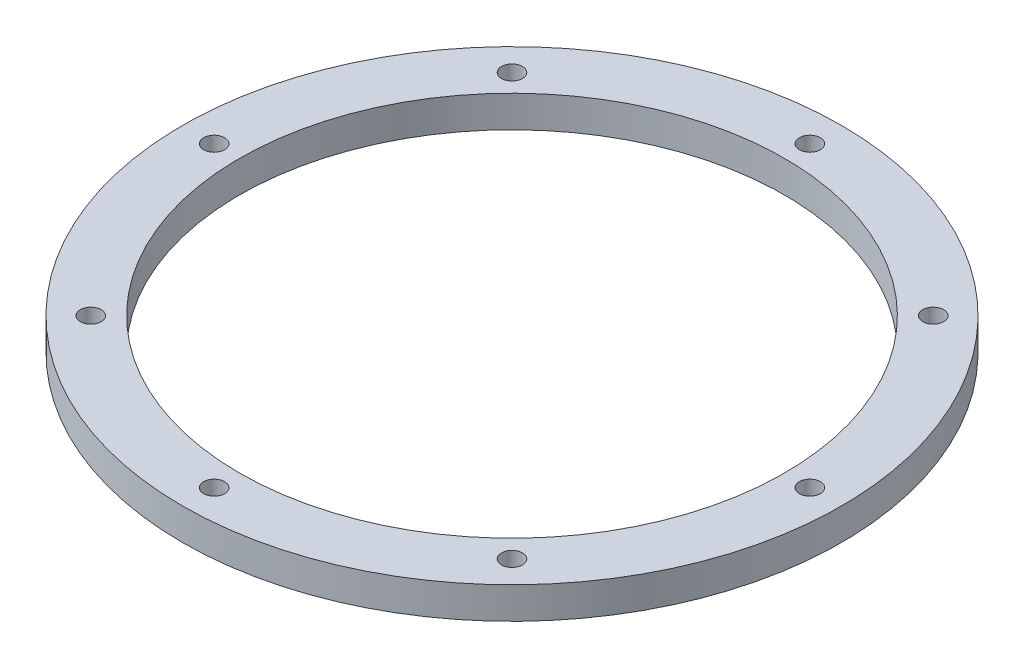
SolidWorks part; units mm, degrees
ref_plane "前视基准面" through (0, 0, 0) normal (0, 0, 1) x (1, 0, 0)
ref_plane "上视基准面" through (0, 0, 0) normal (0, 1, 0) x (1, 0, 0)
ref_plane "右视基准面" through (0, 0, 0) normal (1, 0, 0) x (0, 0, -1)
sketch "草图1" plane through (0, 0, 0) normal (0, 1, 0) x (1, 0, 0)
  circle A0 centre (0, 0) radius 43
  circle A1 centre (0, 0) radius 52
  circle A2 centre (47, 0) radius 1.65
  circle A3 centre (33.234, -33.234) radius 1.65
  circle A4 centre (0, -47) radius 1.65
  circle A5 centre (-33.234, -33.234) radius 1.65
  circle A6 centre (-47, 0) radius 1.65
  circle A7 centre (-33.234, 33.234) radius 1.65
  circle A8 centre (0, 47) radius 1.65
  circle A9 centre (33.234, 33.234) radius 1.65
  point P6 (52, 0)
  point P8 (43, 0)
  dimension "D1" = 86
  dimension "D2" = 4
  dimension "D3" = 5
  dimension "D4" = 3.3
  dimension "D5" = 8
extrude "凸台-拉伸1" add sketch "草图1" along normal blind 5
